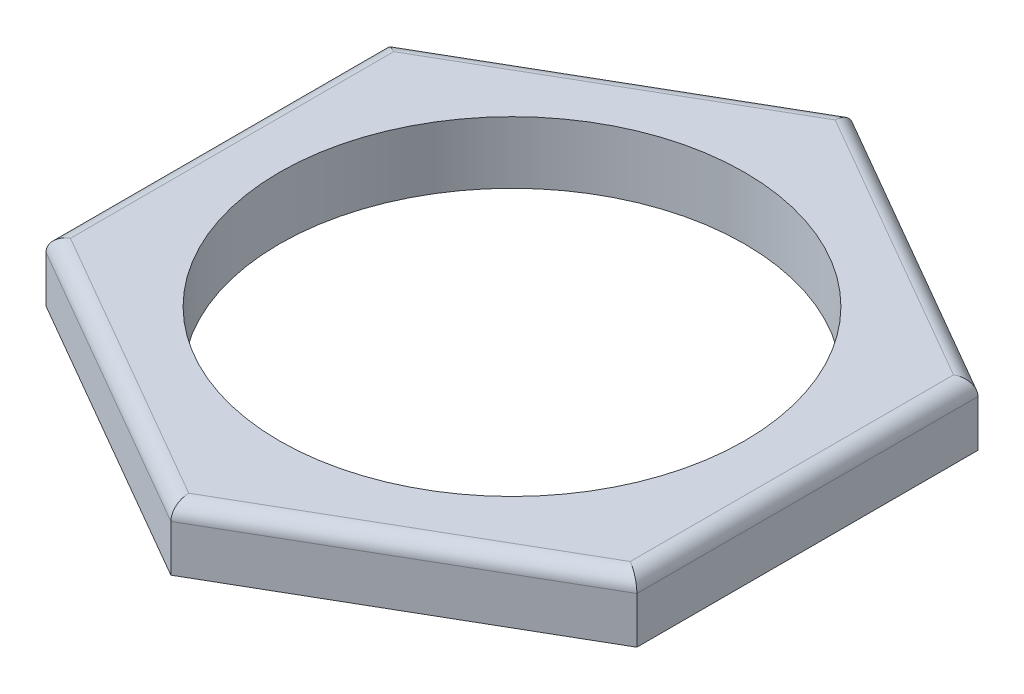
SolidWorks part; units mm, degrees
ref_plane "Front Plane" through (0, 0, 0) normal (0, 0, 1) x (1, 0, 0)
ref_plane "Top Plane" through (0, 0, 0) normal (0, 1, 0) x (1, 0, 0)
ref_plane "Right Plane" through (0, 0, 0) normal (1, 0, 0) x (0, 0, -1)
sketch "Sketch1" plane through (0, 0, 0) normal (0, 1, 0) x (1, 0, 0)
  line L0 (0, 11) -> (9.5263, 5.5)
  line L1 (9.5263, 5.5) -> (9.5263, -5.5)
  line L2 (9.5263, -5.5) -> (0, -11)
  line L3 (0, -11) -> (-9.5263, -5.5)
  line L4 (-9.5263, -5.5) -> (-9.5263, 5.5)
  line L5 (-9.5263, 5.5) -> (0, 11)
  line L6 (0, 11) -> (0, -11) construction
  line L7 (-9.5263, -5.5) -> (9.5263, 5.5) construction
  line L8 (-9.5263, 5.5) -> (9.5263, -5.5) construction
  circle A0 centre (0, 0) radius 7.5
  dimension "D1" = 15
  dimension "D2" = 11
extrude "Boss-Extrude1" add sketch "Sketch1" along normal blind 2
fillet "Fillet1" radius 0.5 6 edges at (4.7631, 2, -8.25) (9.5263, 2, 0) (-4.7631, 2, 8.25) (-9.5263, 2, 0) (-4.7631, 2, -8.25) (4.7631, 2, 8.25)
